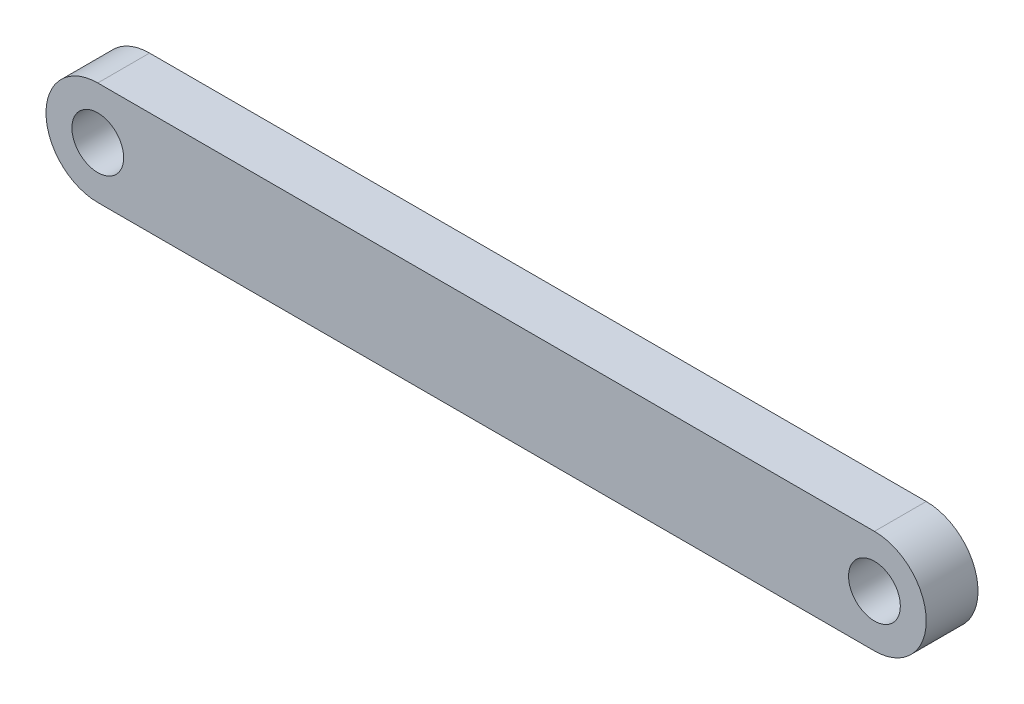
SolidWorks part; units mm, degrees
ref_plane "Front Plane" through (0, 0, 0) normal (0, 0, 1) x (1, 0, 0)
ref_plane "Top Plane" through (0, 0, 0) normal (0, 1, 0) x (1, 0, 0)
ref_plane "Right Plane" through (0, 0, 0) normal (1, 0, 0) x (0, 0, -1)
sketch "Sketch1" plane through (0, 0, 0) normal (0, 0, 1) x (1, 0, 0)
  line L0 (0, 0) -> (150, 0) construction
  line L1 (0, 10) -> (150, 10)
  line L2 (0, -10) -> (150, -10)
  arc A0 (0, 10) -> (0, -10) centre (0, 0) ccw
  arc A1 (150, -10) -> (150, 10) centre (150, 0) ccw
  circle A2 centre (0, 0) radius 5
  circle A3 centre (150, 0) radius 5
  point P3 (75, 0)
  dimension "D2" = 10
  dimension "D1" = 150
  dimension "D3" = 20
extrude "Boss-Extrude1" add sketch "Sketch1" along normal blind 10
